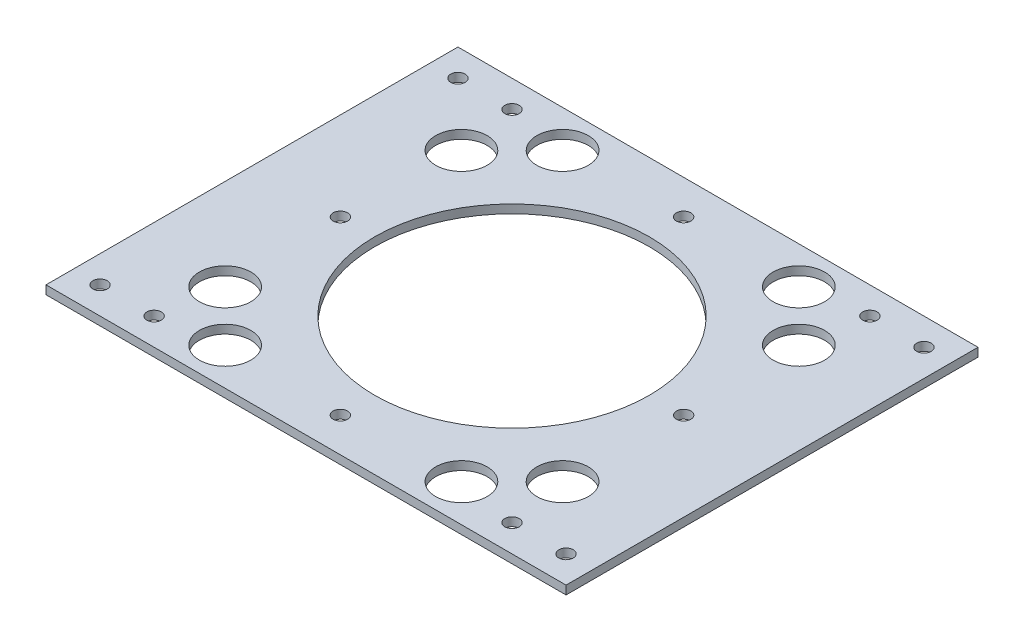
SolidWorks part; units mm, degrees
ref_plane "Front" through (0, 0, 0) normal (0, 0, 1) x (1, 0, 0)
ref_plane "Top" through (0, 0, 0) normal (0, 1, 0) x (1, 0, 0)
ref_plane "Right" through (0, 0, 0) normal (1, 0, 0) x (0, 0, -1)
sketch "Sketch2" plane through (0, 0, 0) normal (0, 1, 0) x (1, 0, 0)
  line L1 (-76.2, -76.2) -> (76.2, -76.2)
  line L2 (-76.2, -76.2) -> (-76.2, 76.2)
  line L3 (-76.2, 76.2) -> (76.2, 76.2)
  line L4 (76.2, -76.2) -> (76.2, 76.2)
  line L5 (-76.2, -76.2) -> (76.2, 76.2) construction
  line L6 (-76.2, 76.2) -> (76.2, -76.2) construction
  circle A0 centre (0, 0) radius 50.8
  point P0 (0, 0)
  dimension "D3" = 101.6
  dimension "D1" = 152.4
  dimension "D2" = 152.4
extrude "Boss-Extrude1" add sketch "Sketch2" along normal blind 3.175
sketch "Sketch3" plane through (0, 3.175, 0) normal (0, 1, 0) x (1, 0, 0)
  line L0 (0, 0) -> (0, -76.2) construction
  line L1 (-76.2, -76.2) -> (76.2, -76.2) construction
  line L2 (0, 0) -> (-76.2, 0) construction
  line L3 (-76.2, 76.2) -> (-76.2, -76.2) construction
  circle A0 centre (-66.2, -66.2) radius 2.665
  circle A1 centre (-66.2, 66.2) radius 2.665
  circle A2 centre (66.2, 66.2) radius 2.665
  circle A3 centre (66.2, -66.2) radius 2.665
  dimension "D1" = 5.33
  dimension "D3" = 10
  dimension "D2" = 10
extrude "Cut-Extrude1" cut sketch "Sketch3" against normal up to next
sketch "Sketch4" plane through (0, 3.175, 0) normal (0, 1, 0) x (1, 0, 0)
  line L0 (0, 0) -> (62.4194, -43.7065) construction
  line L1 (0, 0) -> (43.7065, -62.4194) construction
  line L2 (0, 0) -> (66.2, -66.2) construction
  line L3 (0, 0) -> (76.2, 0) construction
  line L4 (76.2, -76.2) -> (76.2, 76.2) construction
  line L5 (0, 0) -> (0, 76.2) construction
  line L6 (76.2, 76.2) -> (-76.2, 76.2) construction
  circle A2 centre (66.2, -66.2) radius 2.665 construction
  circle A3 centre (62.4194, -43.7065) radius 9.525
  circle A4 centre (43.7065, -62.4194) radius 9.525
  circle A5 centre (43.7065, 62.4194) radius 9.525
  circle A6 centre (62.4194, 43.7065) radius 9.525
  circle A7 centre (-43.7065, 62.4194) radius 9.525
  circle A8 centre (-62.4194, 43.7065) radius 9.525
  circle A9 centre (-43.7065, -62.4194) radius 9.525
  circle A10 centre (-62.4194, -43.7065) radius 9.525
  dimension "D4" = 19.05
  dimension "D1" = 10
  dimension "D2" = 10
  dimension "D3" = 76.2
extrude "Cut-Extrude2" cut sketch "Sketch4" against normal up to next
sketch "Sketch5" plane through (0, 3.175, 0) normal (0, 1, 0) x (1, 0, 0)
  line L0 (0, 0) -> (0, -63.5) construction
  circle A0 centre (0, -63.5) radius 2.665
  circle A2 centre (-63.5, 0) radius 2.665
  circle A3 centre (0, 63.5) radius 2.665
  circle A4 centre (63.5, 0) radius 2.665
  point P13 (0, 0)
  dimension "D2" = 5.33
  dimension "D3" = 4
  dimension "D1" = 63.5
extrude "Cut-Extrude3" cut sketch "Sketch5" against normal up to next
sketch "Sketch6" plane through (76.2, 0, 0) normal (1, 0, 0) x (0, 0, -1)
  line L4 (-76.2, 0) -> (76.2, 0)
  line L5 (76.2, 0) -> (76.2, 3.175)
  line L6 (76.2, 3.175) -> (-76.2, 3.175)
  line L7 (-76.2, 3.175) -> (-76.2, 0)
  line L8 (-76.2, 0) -> (76.2, 0)
  line L9 (76.2, 0) -> (76.2, 3.175)
  line L10 (76.2, 3.175) -> (-76.2, 3.175)
  line L11 (-76.2, 3.175) -> (-76.2, 0)
  dimension "D1" = 0
extrude "Boss-Extrude2" add sketch "Sketch6" along normal blind 20
sketch "Sketch7" plane through (0, 3.175, 0) normal (0, 1, 0) x (1, 0, 0)
  line L0 (66.2, 66.2) -> (86.2, 66.2) construction
  line L1 (66.2, -66.2) -> (86.2, -66.2) construction
  circle A0 centre (86.2, -66.2) radius 2.665
  circle A1 centre (86.2, 66.2) radius 2.665
  circle A2 centre (66.2, -66.2) radius 2.665 construction
  dimension "D1" = 20
extrude "Cut-Extrude4" cut sketch "Sketch7" against normal up to next
mirror "Mirror1" about plane through (0, 0, 0) normal (1, 0, 0) of "Boss-Extrude2", "Cut-Extrude4"
